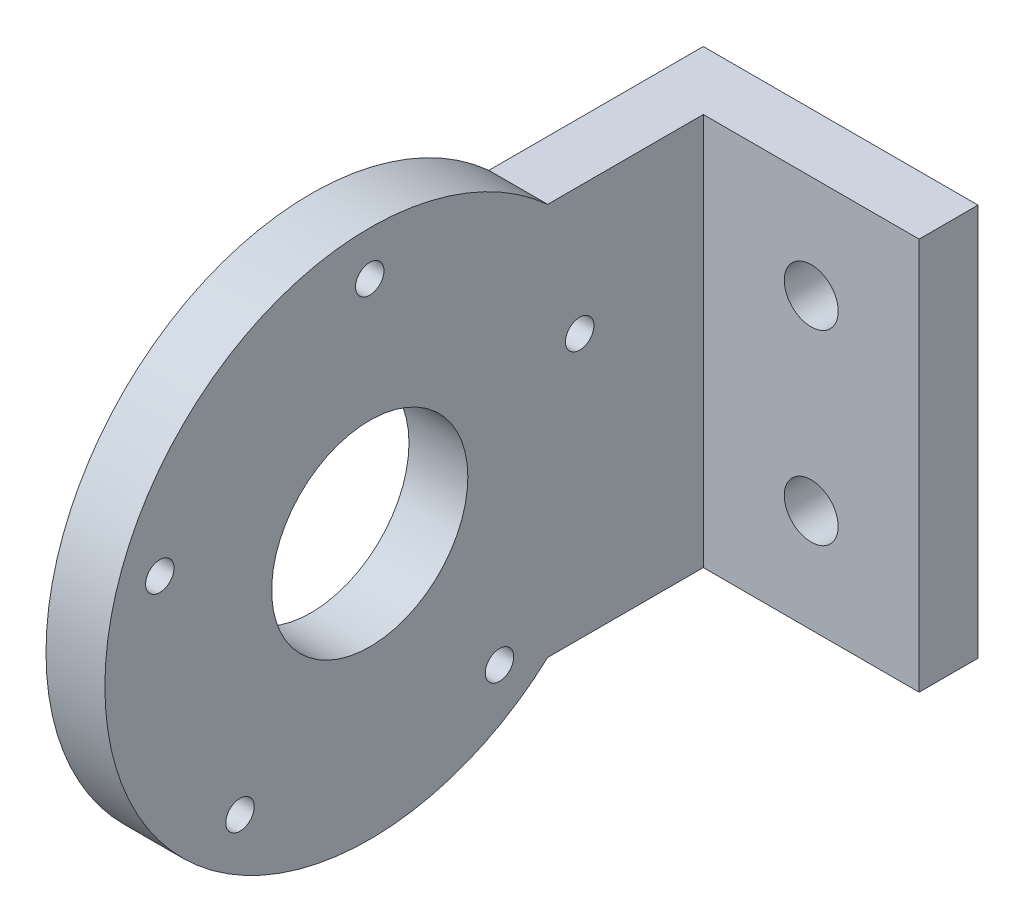
SolidWorks part; units mm, degrees
ref_plane "Front Plane" through (0, 0, 0) normal (0, 0, 1) x (1, 0, 0)
ref_plane "Top Plane" through (0, 0, 0) normal (0, 1, 0) x (1, 0, 0)
ref_plane "Right Plane" through (0, 0, 0) normal (1, 0, 0) x (0, 0, -1)
ref_plane "Plane1" through (221, 0, 0) normal (1, 0, 0) x (0, 0, -1)
sketch "Sketch1" plane through (221, 0, 0) normal (1, 0, 0) x (0, 0, -1)
  circle A0 centre (-300, 300) radius 27
extrude "Boss-Extrude1" add sketch "Sketch1" along normal blind 6
sketch "Sketch2" plane through (221, 0, 0) normal (1, 0, 0) x (0, 0, -1)
  line L0 (-260, 280) -> (-285, 280)
  line L1 (-285, 280) -> (-285, 320)
  line L2 (-285, 320) -> (-260, 320)
  line L3 (-260, 320) -> (-260, 280)
extrude "Boss-Extrude2" add sketch "Sketch2" along normal blind 6
sketch "Sketch3" plane through (221, 0, 0) normal (1, 0, 0) x (0, 0, -1)
  circle A0 centre (-300, 300) radius 10
  circle A1 centre (-300, 322.5) radius 1.45
  circle A2 centre (-278.6012, 306.9529) radius 1.45
  circle A3 centre (-286.7748, 281.7971) radius 1.45
  circle A4 centre (-313.2252, 281.7971) radius 1.45
  circle A5 centre (-321.3988, 306.9529) radius 1.45
extrude "Cut-Extrude1" cut sketch "Sketch3" along normal blind 6
ref_plane "Plane2" through (0, 0, 260) normal (0, 0, 1) x (1, 0, 0)
sketch "Sketch4" plane through (0, 0, 260) normal (0, 0, 1) x (1, 0, 0)
  line L0 (226.99, 280) -> (249, 280)
  line L1 (249, 280) -> (249, 320)
  line L2 (249, 320) -> (226.99, 320)
  line L3 (226.99, 320) -> (226.99, 280)
  circle A0 centre (238, 290.5) radius 2.75
  circle A1 centre (238, 309.5) radius 2.75
extrude "Boss-Extrude3" add sketch "Sketch4" along normal blind 6
